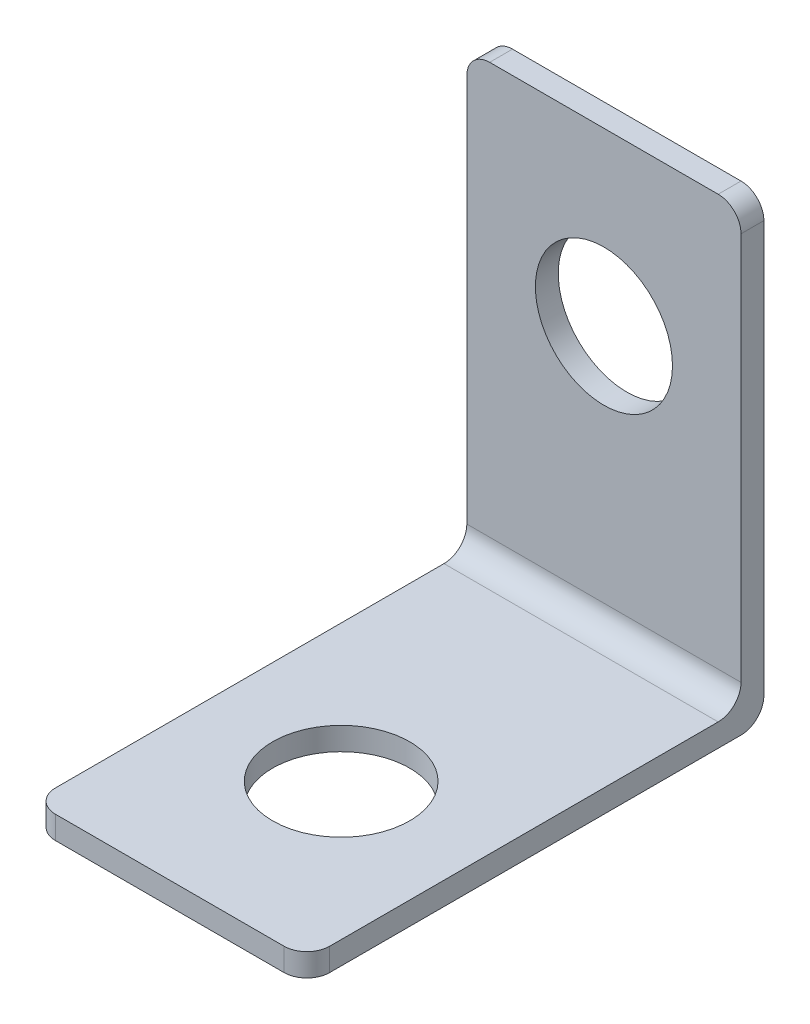
SolidWorks part; units mm, degrees
ref_plane "Plan de face" through (0, 0, 0) normal (0, 0, 1) x (1, 0, 0)
ref_plane "Plan de dessus" through (0, 0, 0) normal (0, 1, 0) x (1, 0, 0)
ref_plane "Plan de droite" through (0, 0, 0) normal (1, 0, 0) x (0, 0, -1)
sketch "Esquisse1" plane through (0, 0, 0) normal (0, 0, 1) x (1, 0, 0)
  line L1 (-6, 0) -> (6, 0)
  line L2 (-6, 0) -> (-6, 20)
  line L3 (-6, 20) -> (6, 20)
  line L4 (6, 0) -> (6, 20)
  circle A0 centre (0, 12.5) radius 3
  point P4 (0, 20)
  dimension "D3" = 6
  dimension "D1" = 20
  dimension "D2" = 12
  dimension "D4" = 7.5
extrude "Boss.-Extru.1" add sketch "Esquisse1" along normal blind 1
sketch "Esquisse2" plane through (0, 0, 1) normal (0, 0, 1) x (1, 0, 0)
  line L0 (6, 0) -> (6, 20) construction
  line L1 (-6, 0) -> (6, 0)
  line L2 (-6, 0) -> (-6, 1)
  line L3 (-6, 1) -> (6, 1)
  line L4 (6, 0) -> (6, 1)
  dimension "D1" = 1
extrude "Boss.-Extru.2" add sketch "Esquisse2" along normal blind 19
sketch "Esquisse3" plane through (0, 1, 0) normal (0, 1, 0) x (1, 0, 0)
  line L0 (6, -20) -> (-6, -20) construction
  circle A0 centre (0, -12.5) radius 3
  point P5 (0, -20)
  dimension "D1" = 6
  dimension "D2" = 7.5
extrude "Enlèv. mat.-Extru.1" cut sketch "Esquisse3" against normal blind 19
fillet "Congé1" radius 1 2 edges at (0, 1, 1) (0, 0, 0)
fillet "Congé2" radius 1 4 edges at (6, 20, 0.5) (-6, 20, 0.5) (-6, 0.5, 20) (6, 0.5, 20)
